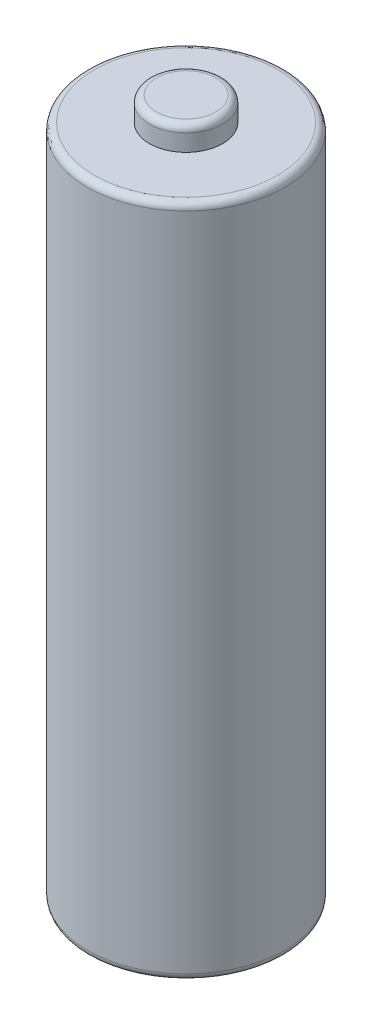
SolidWorks part; units mm, degrees
ref_plane "Front Plane" through (0, 0, 0) normal (0, 0, 1) x (1, 0, 0)
ref_plane "Top Plane" through (0, 0, 0) normal (0, 1, 0) x (1, 0, 0)
ref_plane "Right Plane" through (0, 0, 0) normal (1, 0, 0) x (0, 0, -1)
sketch "Sketch1" plane through (0, 0, 0) normal (0, 1, 0) x (1, 0, 0)
  circle A0 centre (0, 0) radius 7.05
  dimension "D1" = 14.1
extrude "Boss-Extrude2" add sketch "Sketch1" along normal blind 48.25
sketch "Sketch2" plane through (0, 48.25, 0) normal (0, 1, 0) x (1, 0, 0)
  circle A0 centre (0, 0) radius 2.62
  dimension "D1" = 5.24
extrude "Boss-Extrude3" add sketch "Sketch2" along normal blind 1.71
fillet "Fillet1" radius 0.5 3 edges at (0, 49.96, 2.62) (0, 0, 7.05) (0, 48.25, 7.05)
